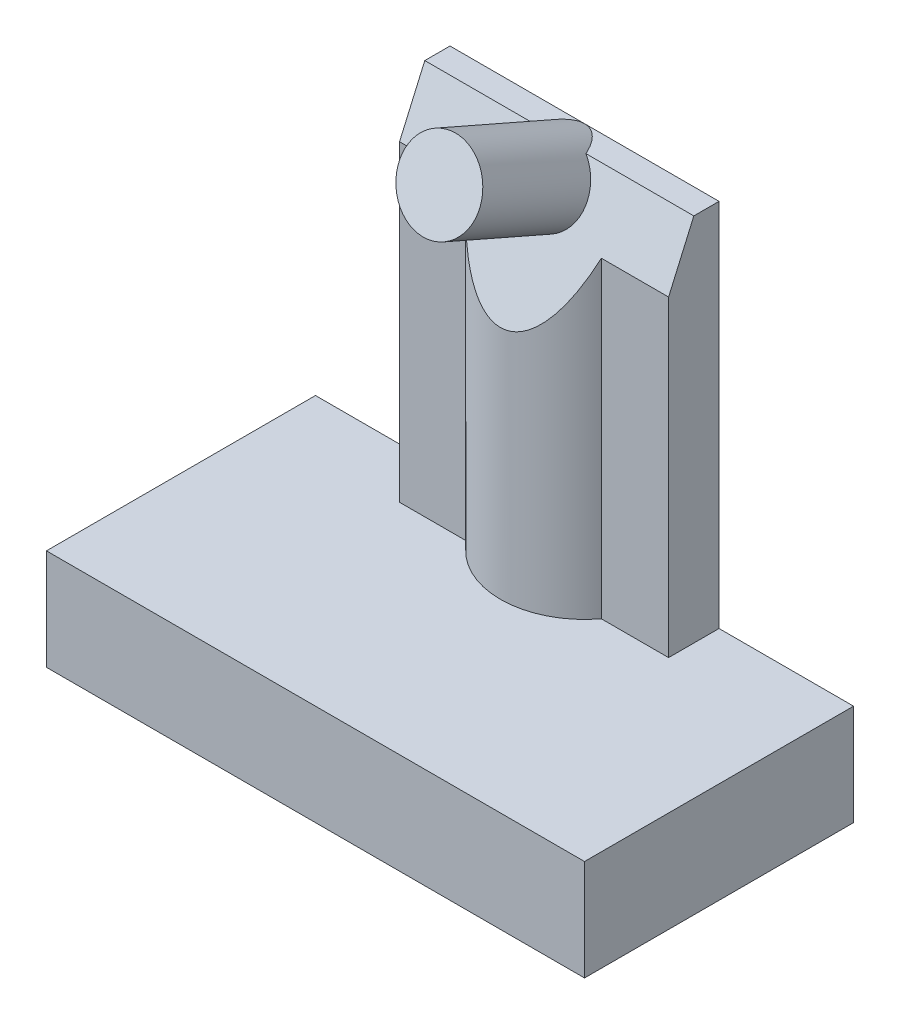
SolidWorks part; units mm, degrees
ref_plane "Front Plane" through (0, 0, 0) normal (0, 0, 1) x (1, 0, 0)
ref_plane "Top Plane" through (0, 0, 0) normal (0, 1, 0) x (1, 0, 0)
ref_plane "Right Plane" through (0, 0, 0) normal (1, 0, 0) x (0, 0, -1)
sketch "Sketch1" plane through (0, 0, 0) normal (0, 1, 0) x (1, 0, 0)
  line L1 (8, -4) -> (-8, -4)
  line L2 (8, -4) -> (8, 4)
  line L3 (8, 4) -> (-8, 4)
  line L4 (-8, -4) -> (-8, 4)
  line L5 (8, -4) -> (-8, 4) construction
  line L6 (8, 4) -> (-8, -4) construction
  point P0 (0, 0)
  dimension "D1" = 16
  dimension "D2" = 8
extrude "Boss-Extrude1" add sketch "Sketch1" along normal blind 3 contours L4 L3 L2 L1
shell "Shell1" thickness 1
sketch "Sketch3" plane through (0, 2, 0) normal (0, -1, 0) x (1, 0, 0)
  circle A0 centre (0, 0) radius 1.5
  circle A1 centre (0, 0) radius 0.8
  dimension "D1" = 3
  dimension "D2" = 1.6
extrude "Boss-Extrude2" add sketch "Sketch3" along normal blind 2
sketch "Sketch4" plane through (0, 3, 0) normal (0, 1, 0) x (1, 0, 0)
  line L1 (-4, 4) -> (4, 4)
  line L2 (8, 4) -> (-8, 4) construction
  line L3 (4, 4) -> (4, 2.5)
  line L4 (4, 2.5) -> (2, 2.5)
  line L5 (-4, 2.5) -> (-2, 2.5)
  line L6 (-4, 4) -> (-4, 2.5)
  arc A0 (-2, 2.5) -> (2, 2.5) centre (0, 4) ccw
  point P2 (0, 0)
  point P3 (0, 0)
  point P8 (0, 4)
  point P11 (0, 4)
  point P12 (0, 4)
  point P15 (0, 4)
  point P16 (0, 3.8822)
  dimension "D1" = 5
  dimension "D2" = 4
  dimension "D3" = 1.5
  dimension "D4" = 1.5
  dimension "D5" = 2
extrude "Boss-Extrude3" add sketch "Sketch4" along normal blind 11
sketch "Sketch5" plane through (4, 0, 0) normal (1, 0, 0) x (0, 0, -1)
  line L0 (3.25, 14) -> (1.5, 14)
  line L1 (2.5, 14) -> (4, 14) construction
  line L2 (1.5, 14) -> (1.5, 10)
  line L3 (1.5, 14) -> (1.5, 3) construction
  line L4 (1.5, 10) -> (3.25, 14)
  dimension "D1" = 4
extrude "Cut-Extrude1" cut sketch "Sketch5" against normal up to next
sketch "Sketch6" plane through (0, 1.0557, 2.4131) normal (0, 0.4008, 0.9162) x (1, 0, 0)
  line L0 (4, 14.4295) -> (-4, 14.4295) construction
  circle A0 centre (0, 13.2295) radius 1.2
  point P4 (0, 0)
  dimension "D1" = 2.4
extrude "Boss-Extrude5" add sketch "Sketch6" along normal blind 3.5 and the other way up to next
